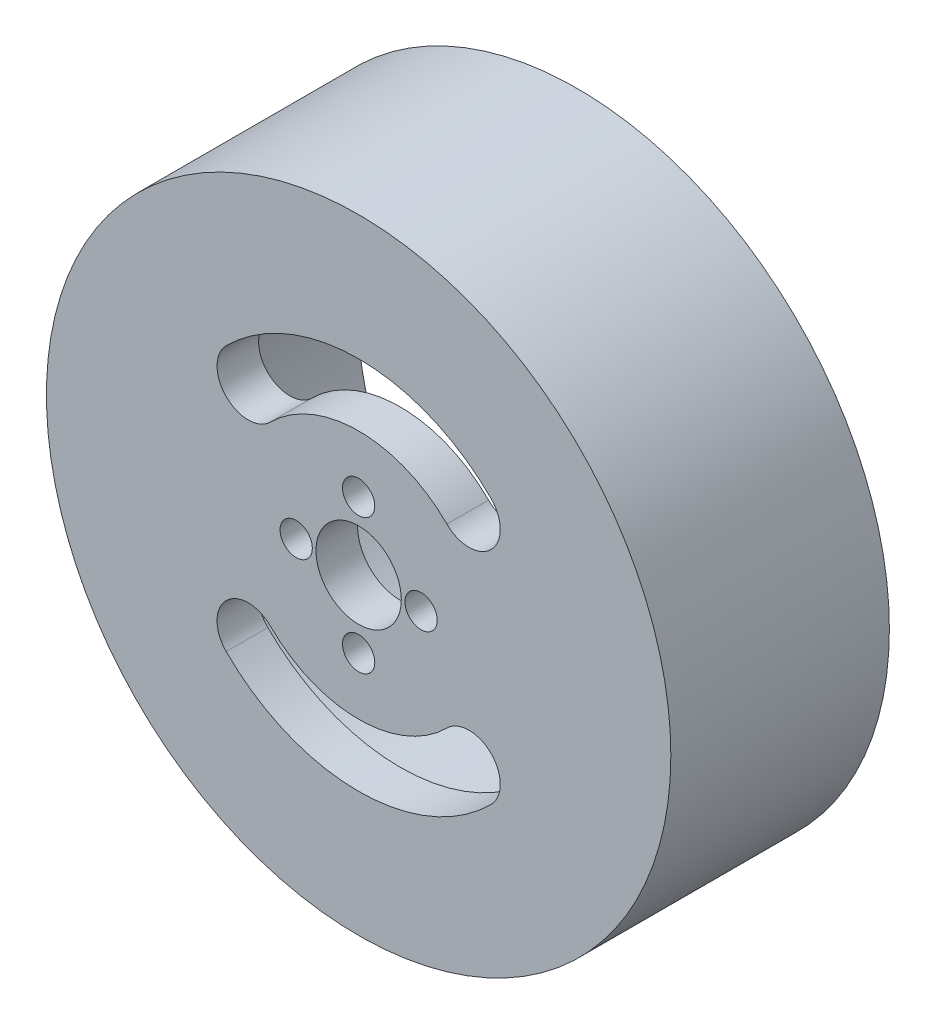
SolidWorks part; units mm, degrees
ref_plane "Front Plane" through (0, 0, 0) normal (0, 0, 1) x (1, 0, 0)
ref_plane "Top Plane" through (0, 0, 0) normal (0, 1, 0) x (1, 0, 0)
ref_plane "Right Plane" through (0, 0, 0) normal (1, 0, 0) x (0, 0, -1)
sketch "Sketch1" plane through (0, 0, 0) normal (0, 0, 1) x (1, 0, 0)
  arc A0 (0, -30) -> (0, 30) centre (0, 0) ccw construction
  circle A1 centre (0, 0) radius 30
  arc A2 (12.7279, 12.7279) -> (0, 18) centre (0, 0) ccw construction
  arc A3 (0, 18) -> (-12.7279, 12.7279) centre (0, 0) ccw construction
  arc A4 (-12.7279, 12.7279) -> (-8.4853, 8.4853) centre (-10.6066, 10.6066) ccw construction
  arc A5 (0, 12) -> (-8.4853, 8.4853) centre (0, 0) ccw construction
  arc A6 (8.4853, 8.4853) -> (0, 12) centre (0, 0) ccw construction
  arc A7 (8.4853, 8.4853) -> (12.7279, 12.7279) centre (10.6066, 10.6066) ccw construction
  arc A8 (12.7279, -12.7279) -> (10.6066, -7.6066) centre (10.6066, -10.6066) ccw construction
  arc A9 (10.6066, -7.6066) -> (8.4853, -8.4853) centre (10.6066, -10.6066) ccw construction
  arc A10 (-8.4853, -8.4853) -> (8.4853, -8.4853) centre (0, 0) ccw construction
  arc A11 (-8.4853, -8.4853) -> (-10.6066, -7.6066) centre (-10.6066, -10.6066) ccw construction
  arc A12 (-10.6066, -7.6066) -> (-12.7279, -12.7279) centre (-10.6066, -10.6066) ccw construction
  arc A13 (-12.7279, -12.7279) -> (12.7279, -12.7279) centre (0, 0) ccw construction
  arc A14 (-12.7279, -12.7279) -> (12.7279, -12.7279) centre (0, 0) ccw
  arc A15 (-10.6066, -7.6066) -> (-12.7279, -12.7279) centre (-10.6066, -10.6066) ccw
  arc A16 (-8.4853, -8.4853) -> (-10.6066, -7.6066) centre (-10.6066, -10.6066) ccw
  arc A17 (-8.4853, -8.4853) -> (8.4853, -8.4853) centre (0, 0) ccw
  arc A18 (10.6066, -7.6066) -> (8.4853, -8.4853) centre (10.6066, -10.6066) ccw
  arc A19 (12.7279, -12.7279) -> (10.6066, -7.6066) centre (10.6066, -10.6066) ccw
  arc A20 (8.4853, 8.4853) -> (12.7279, 12.7279) centre (10.6066, 10.6066) ccw
  arc A21 (8.4853, 8.4853) -> (0, 12) centre (0, 0) ccw
  arc A22 (0, 12) -> (-8.4853, 8.4853) centre (0, 0) ccw
  arc A23 (-12.7279, 12.7279) -> (-8.4853, 8.4853) centre (-10.6066, 10.6066) ccw
  arc A24 (0, 18) -> (-12.7279, 12.7279) centre (0, 0) ccw
  arc A25 (12.7279, 12.7279) -> (0, 18) centre (0, 0) ccw
  arc A26 (0, -4.95) -> (0, -8.05) centre (0, -6.5) ccw construction
  arc A27 (0, -8.05) -> (0, -4.95) centre (0, -6.5) ccw construction
  arc A28 (6, 1.55) -> (6, -1.55) centre (6, 0) ccw construction
  arc A29 (6, -1.55) -> (6, 1.55) centre (6, 0) ccw construction
  arc A30 (-6, 1.55) -> (-6, -1.55) centre (-6, 0) ccw construction
  arc A31 (-6, -1.55) -> (-6, 1.55) centre (-6, 0) ccw construction
  arc A32 (0, 4.95) -> (0, 8.05) centre (0, 6.5) ccw construction
  arc A33 (0, 8.05) -> (0, 4.95) centre (0, 6.5) ccw construction
  arc A34 (0, 4.1) -> (0, -4.1) centre (0, 0) ccw construction
  arc A35 (0, -4.1) -> (0, 4.1) centre (0, 0) ccw construction
  arc A36 (0, -4.95) -> (0, -8.05) centre (0, -6.5) ccw
  arc A37 (0, -8.05) -> (0, -4.95) centre (0, -6.5) ccw
  arc A38 (6, 1.55) -> (6, -1.55) centre (6, 0) ccw
  arc A39 (6, -1.55) -> (6, 1.55) centre (6, 0) ccw
  arc A40 (-6, 1.55) -> (-6, -1.55) centre (-6, 0) ccw
  arc A41 (-6, -1.55) -> (-6, 1.55) centre (-6, 0) ccw
  arc A42 (0, 4.95) -> (0, 8.05) centre (0, 6.5) ccw
  arc A43 (0, 8.05) -> (0, 4.95) centre (0, 6.5) ccw
  arc A44 (0, 4.1) -> (0, -4.1) centre (0, 0) ccw
  arc A45 (0, -4.1) -> (0, 4.1) centre (0, 0) ccw
  point P3 (0.707, -29.9917)
extrude "Boss-Extrude1" add sketch "Sketch1" against normal up to vertex (4 mm away)
sketch "Sketch2" plane through (0, 0, -21) normal (0, 0, -1) x (-1, 0, 0)
  arc A0 (0, 21) -> (0, -21) centre (0, 0) ccw construction
  arc A1 (0, -21) -> (0, 21) centre (0, 0) ccw construction
  arc A2 (0, -30) -> (0, 30) centre (0, 0) ccw
  arc A3 (0, 30) -> (0, -30) centre (0, 0) ccw
  arc A4 (0, -30) -> (0, 30) centre (0, 0) ccw
  arc A5 (0, 30) -> (0, -30) centre (0, 0) ccw
  arc A6 (0, 21) -> (0, -21) centre (0, 0) ccw
  arc A7 (0, -21) -> (0, 21) centre (0, 0) ccw
  dimension "D1" = 0
extrude "Boss-Extrude2" add sketch "Sketch2" against normal up to vertex (17 mm away)
